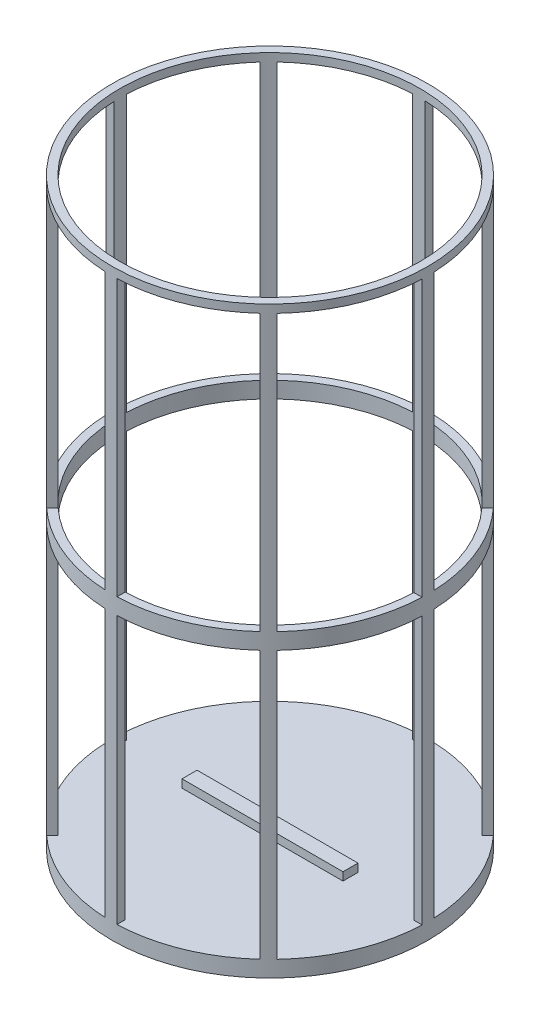
SolidWorks part; units mm, degrees
ref_plane "Front Plane" through (0, 0, 0) normal (0, 0, 1) x (1, 0, 0)
ref_plane "Top Plane" through (0, 0, 0) normal (0, 1, 0) x (1, 0, 0)
ref_plane "Right Plane" through (0, 0, 0) normal (1, 0, 0) x (0, 0, -1)
sketch "Sketch1" plane through (0, 0, 0) normal (0, 1, 0) x (1, 0, 0)
  circle A0 centre (0, 0) radius 49.53
  circle A1 centre (0, 0) radius 46.99
  dimension "D1" = 99.06
  dimension "D2" = 93.98
extrude "Boss-Extrude1" add sketch "Sketch1" along normal mid plane 365.76
sketch "Sketch2" plane through (0, 0, 0) normal (0, 1, 0) x (1, 0, 0)
  line L0 (0, -49.53) -> (0, 49.53) construction
  line L1 (49.53, 0) -> (-49.53, 0) construction
  line L2 (36.1361, -33.8733) -> (-33.8733, 36.1361)
  line L3 (49.4953, -1.8543) -> (-49.4953, -1.8543)
  line L5 (49.4914, 1.9557) -> (-49.4914, 1.9557)
  line L7 (49.5079, -1.4801) -> (-49.5079, 1.4801) construction
  line L8 (49.5079, 1.4801) -> (-49.5079, -1.4801) construction
  line L10 (-2.2251, -49.48) -> (-2.2251, 49.48)
  line L12 (1.5849, -49.5046) -> (1.5849, 49.5046)
  line L13 (-2.0946, -49.4857) -> (2.0946, 49.4857) construction
  line L14 (-2.0946, 49.4857) -> (2.0946, -49.4857) construction
  line L17 (33.4254, -36.5508) -> (-36.5508, 33.4254)
  line L18 (36.2203, -33.7833) -> (-36.2203, 33.7833) construction
  line L19 (-33.7833, 36.2203) -> (33.7833, -36.2203) construction
  line L20 (-36.2459, -33.7558) -> (33.7558, 36.2459)
  line L23 (-33.544, -36.4421) -> (36.4421, 33.544)
  line L24 (-35.9086, -34.1144) -> (35.9086, 34.1144) construction
  line L25 (34.1144, 35.9086) -> (-34.1144, -35.9086) construction
  line L26 (42.4888, -20.0689) -> (-44.235, 15.8533)
  line L29 (43.9751, -16.5606) -> (-42.8052, 19.385)
  line L30 (42.7791, -19.4425) -> (-42.7791, 19.4425) construction
  line L31 (-43.9973, 16.5014) -> (43.9973, -16.5014) construction
  line L32 (19.1177, -42.9252) -> (-16.8344, 43.871)
  line L35 (15.577, -44.333) -> (-20.3336, 42.3628)
  line L36 (19.8255, -42.6029) -> (-19.8255, 42.6029) construction
  line L37 (-16.1061, 44.1436) -> (16.1061, -44.1436) construction
  line L38 (-16.6796, -43.9301) -> (19.2689, 42.8575)
  line L41 (-20.184, -42.4343) -> (15.7333, 44.2778)
  line L42 (-16.127, -44.1359) -> (16.127, 44.1359) construction
  line L43 (19.8053, 42.6123) -> (-19.8053, -42.6123) construction
  line L44 (-44.26, -15.7832) -> (42.457, 20.1362)
  line L47 (-42.8358, -19.3171) -> (43.9488, 16.6302)
  line L48 (-44.0599, -16.3335) -> (44.0599, 16.3335) construction
  line L49 (42.7046, 19.6055) -> (-42.7046, -19.6055) construction
  circle A0 centre (0, 0) radius 49.53
  circle A1 centre (0, 0) radius 46.99
  point P7 (0, 0)
  point P10 (0, 0)
  dimension "D1" = 45
  dimension "D2" = 45
  dimension "D3" = 22.5
  dimension "D4" = 22.5
  dimension "D5" = 22.5
  dimension "D6" = 22.5
  dimension "D7" = 3.81
  dimension "D8" = 3.81
  dimension "D9" = 3.81
  dimension "D10" = 3.81
  dimension "D11" = 3.81
  dimension "D12" = 3.81
  dimension "D13" = 3.81
  dimension "D14" = 3.81
extrude "Cut-Extrude1" cut sketch "Sketch2" against normal mid plane 355.6 contours A1 L10 A0 L2 | A1 L17 A0 L5 | A1 L3 A0 L20 | A1 L23 A0 L10 | A1 L12 A0 L17 | A1 L2 A0 L3 | A1 L5 A0 L23 | A1 L20 A0 L12 L35
ref_plane "Plane1" through (0, 91.44, 0) normal (0, 1, 0) x (1, 0, 0)
sketch "Sketch3" plane through (0, 91.44, 0) normal (0, 1, 0) x (1, 0, 0)
  circle A0 centre (0, 0) radius 46.99
  circle A1 centre (0, 0) radius 49.53
extrude "Boss-Extrude2" add sketch "Sketch3" along normal mid plane 5.08
mirror "Mirror1" about plane through (0, 0, 0) normal (0, 1, 0) of "Boss-Extrude2"
sketch "Sketch4" plane through (0, 0, 0) normal (0, 1, 0) x (1, 0, 0)
  circle A0 centre (0, 0) radius 46.99
  circle A1 centre (0, 0) radius 49.53
extrude "Boss-Extrude3" add sketch "Sketch4" along normal mid plane 5.08
sketch "Sketch5" plane through (0, -182.88, 0) normal (0, -1, 0) x (1, 0, 0)
  circle A0 centre (0, 0) radius 49.53
extrude "Boss-Extrude4" add sketch "Sketch5" against normal blind 5.08
sketch "Sketch6" plane through (0, -177.8, 0) normal (0, 1, 0) x (1, 0, 0)
  line L0 (0, -49.53) -> (0, 49.53) construction
  line L1 (49.53, 0) -> (-49.53, 0) construction
  line L3 (25.2095, -2.3495) -> (-25.2095, -2.3495)
  line L4 (25.2095, -2.3495) -> (25.2095, 2.3495)
  line L5 (25.2095, 2.3495) -> (-25.2095, 2.3495)
  line L6 (-25.2095, -2.3495) -> (-25.2095, 2.3495)
  line L7 (25.2095, -2.3495) -> (-25.2095, 2.3495) construction
  line L8 (25.2095, 2.3495) -> (-25.2095, -2.3495) construction
  circle A0 centre (0, 0) radius 49.53 construction
  point P0 (0, 0)
  point P7 (0, 0)
  point P11 (0, 0)
  dimension "D1" = 50.419
  dimension "D2" = 4.699
extrude "Boss-Extrude5" add sketch "Sketch6" along normal blind 2.54
sketch "Sketch7" plane through (0, 182.88, 0) normal (0, 1, 0) x (1, 0, 0)
  line L0 (0, 49.53) -> (0, -49.53) construction
  line L1 (49.53, 0) -> (46.99, 0) construction
  line L2 (0, 0) -> (-49.53, 0) construction
  circle A1 centre (0, 0) radius 49.53 construction
  circle A2 centre (0, 0) radius 46.99 construction
  circle A3 centre (48.26, 0) radius 0.8255
  point P8 (0, 0)
  point P11 (0, 0)
  dimension "D1" = 1.651
  dimension "D2" = 1.27
extrude "Boss-Extrude6" add sketch "Sketch7" along normal blind 2.54
pattern_circular "CirPattern2" count 8 over 360 about axis through (0, 0, 0) along (0, 1, 0) of "Boss-Extrude6"
sketch "Sketch8" plane through (0, 0, 0) normal (0, 0, 1) x (1, 0, 0)
  line L0 (-49.4953, -2.54) -> (-36.2459, -2.54) construction
  line L1 (57.4041, 0) -> (-53.7114, 0)
  line L2 (57.4041, 0) -> (57.4041, 193.5816)
  line L3 (57.4041, 193.5816) -> (-53.7114, 193.5816)
  line L4 (-53.7114, 0) -> (-53.7114, 193.5816)
  dimension "D1" = 2.54
extrude "Cut-Extrude2" cut sketch "Sketch8" against normal through all both and the other way through all
